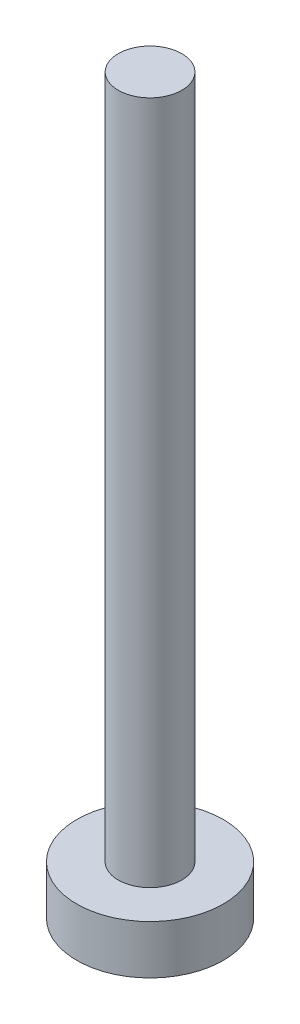
SolidWorks part; units mm, degrees
ref_plane "Front Plane" through (0, 0, 0) normal (0, 0, 1) x (1, 0, 0)
ref_plane "Top Plane" through (0, 0, 0) normal (0, 1, 0) x (1, 0, 0)
ref_plane "Right Plane" through (0, 0, 0) normal (1, 0, 0) x (0, 0, -1)
sketch "Sketch1" plane through (0, 0, 0) normal (0, 1, 0) x (1, 0, 0)
  circle A0 centre (0, 0) radius 0.65
  circle A1 centre (0, 0) radius 1.5
  dimension "D1" = 1.3
  dimension "D2" = 3
extrude "Boss-Extrude1" add sketch "Sketch1" along normal blind 14 contours A0
sketch "Sketch2" plane through (0, 0, 0) normal (0, -1, 0) x (1, 0, 0)
  circle A0 centre (0, 0) radius 1.5
  dimension "D1" = 3
extrude "Boss-Extrude2" add sketch "Sketch2" along normal blind 1
